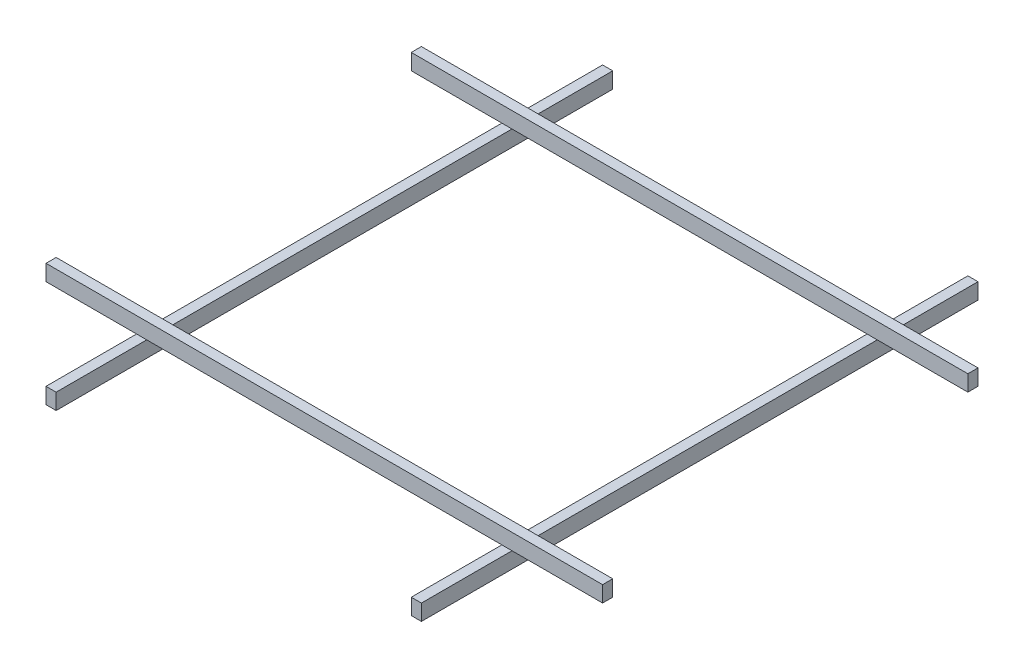
SolidWorks part; units mm, degrees
material "Doug Fir"
ref_plane "Front Plane" through (0, 0, 0) normal (0, 0, 1) x (1, 0, 0)
ref_plane "Top Plane" through (0, 0, 0) normal (0, 1, 0) x (1, 0, 0)
ref_plane "Right Plane" through (0, 0, 0) normal (1, 0, 0) x (0, 0, -1)
sketch "Lower Level" plane through (0, 0, 0) normal (0, 1, 0) x (1, 0, 0)
  line L0 (533.4, 0) -> (533.4, 4876.8)
  line L1 (3733.8, 0) -> (3733.8, 4876.8)
  line L2 (533.4, 2438.4) -> (3733.8, 2438.4) construction
  point P7 (2133.6, 2438.4)
  dimension "D1" = 4876.8
  dimension "D2" = 1600.2
ref_plane "Plane2" through (0, 139.7, 0) normal (0, 1, 0) x (1, 0, 0)
sketch "Sketch12" plane through (0, 139.7, 0) normal (0, 1, 0) x (1, 0, 0)
  line L0 (-304.8, 4038.6) -> (4572, 4038.6)
  line L1 (4572, 838.2) -> (-304.8, 838.2)
  line L2 (2133.6, 4038.6) -> (2133.6, 838.2) construction
  point P0 (2133.6, 2438.4)
  point P6 (2133.6, 838.2)
  point P7 (2133.6, 4038.6)
  point P10 (2133.6, 2438.4)
  dimension "D1" = 4876.8
  dimension "D2" = 1600.2
other "Profiles 4X6(1)"
ref_plane "Plane1" through (533.4, 0, 0) normal (0, 0, -1) x (-1, 0, 0)
sketch "Sketch1" plane through (533.4, 0, 0) normal (0, 0, -1) x (-1, 0, 0)
  line L1 (-44.45, 69.85) -> (44.45, 69.85)
  line L2 (-44.45, 69.85) -> (-44.45, -69.85)
  line L3 (-44.45, -69.85) -> (44.45, -69.85)
  line L4 (44.45, 69.85) -> (44.45, -69.85)
  line L5 (-44.45, 69.85) -> (44.45, -69.85) construction
  line L6 (-44.45, -69.85) -> (44.45, 69.85) construction
  point P0 (0, 0)
  point P6 (0, 69.85)
  point P7 (0, -69.85)
  point P8 (44.45, 0)
  point P9 (-44.45, 0)
  point P10 (0, 0)
  dimension "D1" = 88.9
  dimension "D2" = 139.7
sketch3d "3DSketch2"
  line L0 (2133.6, 139.7, -2438.4) -> (2133.6, 0, -2438.4)
  line L1 (533.4, 0, -2438.4) -> (3733.8, 0, -2438.4) construction
equation "\"Width\" = 63"
equation "\"Length\"=192"
equation "\"D1@Lower Level\"=\"Length\""
equation "\"D2@Lower Level\"=\"Width\""
equation "\"D1@Sketch12\"=\"Length\""
equation "\"D2@Sketch12\"=\"Width\""
